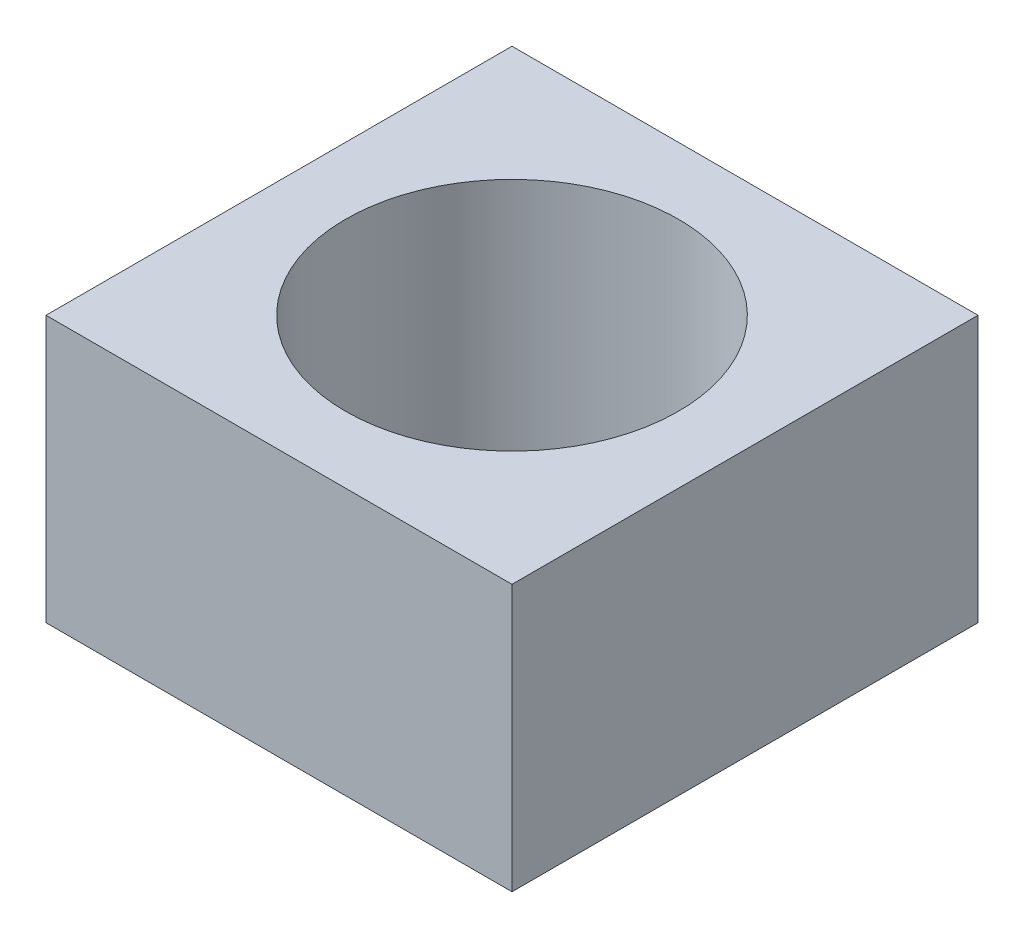
SolidWorks part; units mm, degrees
ref_plane "前视基准面" through (0, 0, 0) normal (0, 0, 1) x (1, 0, 0)
ref_plane "上视基准面" through (0, 0, 0) normal (0, 1, 0) x (1, 0, 0)
ref_plane "右视基准面" through (0, 0, 0) normal (1, 0, 0) x (0, 0, -1)
other "Configuration Table"
sketch "草图1" plane through (0, 0, 0) normal (0, 1, 0) x (1, 0, 0)
  line L1 (0, 0) -> (7, 0)
  line L2 (0, 0) -> (0, 7)
  line L3 (0, 7) -> (7, 7)
  line L4 (7, 0) -> (7, 7)
  circle A0 centre (3.5, 3.5) radius 2.5
  point P7 (3.5, 7)
  point P8 (0, 3.5)
  dimension "D3" = 5
  dimension "D4" = 0
  dimension "D5" = 0
  dimension "D1" = 7
  dimension "D2" = 7
extrude "凸台-拉伸1" add sketch "草图1" along normal blind 4
